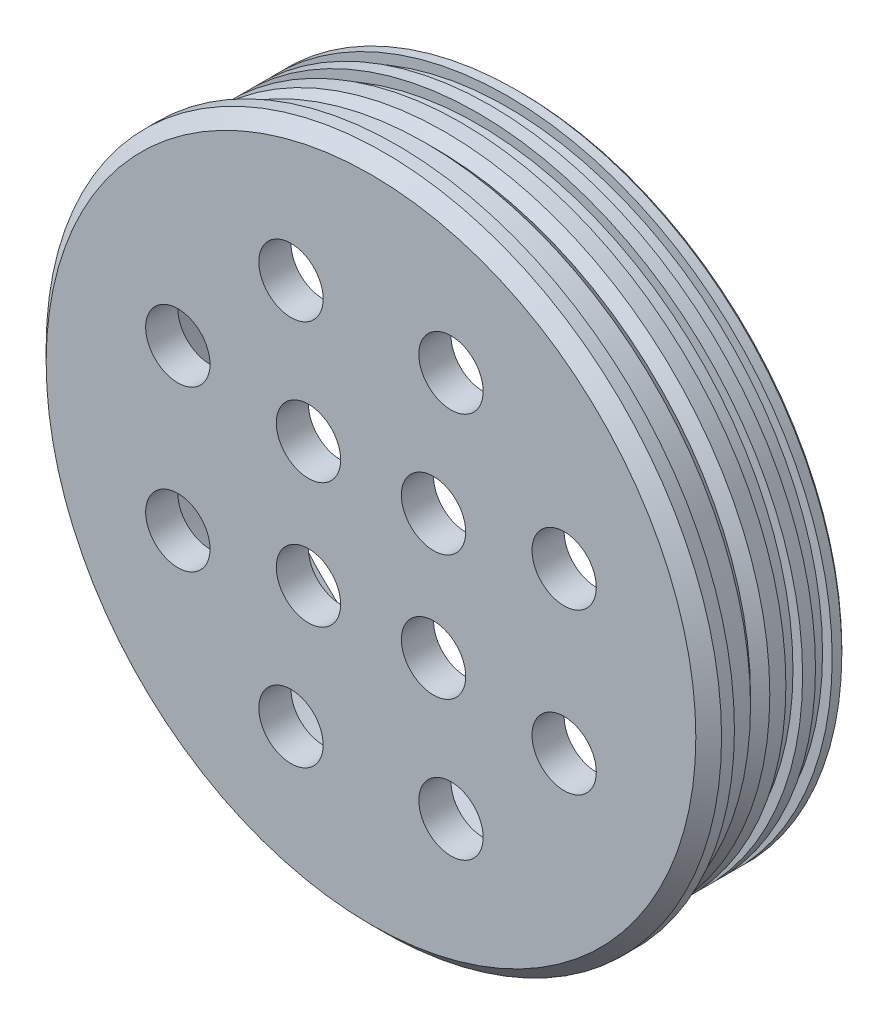
SolidWorks part; units mm, degrees
ref_plane "Спереди" through (0, 0, 0) normal (0, 0, 1) x (1, 0, 0)
ref_plane "Сверху" through (0, 0, 0) normal (0, 1, 0) x (1, 0, 0)
ref_plane "Справа" through (0, 0, 0) normal (1, 0, 0) x (0, 0, -1)
sketch "Эскиз2" plane through (0, 0, 0) normal (0, 1, 0) x (1, 0, 0)
  line L0 (0, 0) -> (0, 296960.8862) construction
  line L1 (0, 0) -> (0, 5)
  line L2 (0, 5) -> (-43.5, 5)
  line L3 (-43.5, 5) -> (-43.5, 23.2)
  line L4 (-43.5, 23.2) -> (-50, 23.2)
  line L5 (-50.5, 22.7) -> (-50.5, 21.2)
  line L6 (-50.5, 16.6) -> (-49, 16.6)
  line L7 (-49, 16.6) -> (-49, 14)
  line L8 (-49, 14) -> (-50.5, 14)
  line L9 (-50.5, 14) -> (-50.5, 11.5)
  line L10 (-18.3864, 0) -> (0, 0)
  line L11 (-50.5, 4) -> (-52.5, 4)
  line L12 (-52.5, 4) -> (-52.5, 0)
  line L13 (-52.5, 0) -> (-18.3864, 0)
  line L14 (-22, 0) -> (-2.5926, 0) construction
  line L15 (-50.5, 8.5) -> (-49, 10)
  line L16 (-49, 10) -> (-50.5, 11.5)
  line L17 (-50.5, 8.5) -> (-50.5, 4)
  line L18 (-50.5, 18.6) -> (-49, 18.6)
  line L19 (-49, 18.6) -> (-49, 21.2)
  line L20 (-49, 21.2) -> (-50.5, 21.2)
  line L21 (-50.5, 18.6) -> (-50.5, 16.6)
  line L22 (-50, 23.2) -> (-50.5, 22.7)
  line L23 (-50.5, 22.7) -> (-43.5, 22.7) construction
  line L24 (-47, 24.4497) -> (-47, 20.3957) construction
  point P8 (-50.5, 23.2)
  dimension "D2" = 5
  dimension "D3" = 105
  dimension "D4" = 1.5
  dimension "D5" = 2.6
  dimension "D6" = 1.5
  dimension "D7" = 10
  dimension "D8" = 2
  dimension "D9" = 2
  dimension "D10" = 7
  dimension "D11" = 4
  dimension "D12" = 4
  dimension "D13" = 2
  dimension "D14" = 2.6
  dimension "D15" = 1.5
  dimension "D16" = 3.5
revolve "Повернуть1" add sketch "Эскиз2" angle 360 about L0
chamfer "Фаска1" distance 2 angle 45 1 edges at (52.5, 0, 0)
sketch "Эскиз4" plane through (0, 0, 0) normal (0, 0, 1) x (1, 0, 0)
  line L0 (0, 0) -> (64.1004, 0) construction
  line L1 (30.0261, 12.4372) -> (30.0261, -12.4372) construction
  line L3 (-9.7227, -9.7227) -> (9.7227, -9.7227) construction
  line L4 (-9.7227, -9.7227) -> (-9.7227, 9.7227) construction
  line L5 (-9.7227, 9.7227) -> (9.7227, 9.7227) construction
  line L6 (9.7227, -9.7227) -> (9.7227, 9.7227) construction
  line L7 (-9.7227, -9.7227) -> (9.7227, 9.7227) construction
  line L8 (-9.7227, 9.7227) -> (9.7227, -9.7227) construction
  circle A0 centre (-12.4372, -30.0261) radius 5
  circle A1 centre (-30.0261, 12.4372) radius 5
  circle A2 centre (-12.4372, 30.0261) radius 5
  circle A3 centre (12.4372, 30.0261) radius 5
  circle A4 centre (30.0261, 12.4372) radius 5
  circle A5 centre (30.0261, -12.4372) radius 5
  circle A6 centre (12.4372, -30.0261) radius 5
  circle A7 centre (-30.0261, -12.4372) radius 5
  circle A8 centre (-9.7227, 9.7227) radius 5
  circle A9 centre (9.7227, 9.7227) radius 5
  circle A10 centre (9.7227, -9.7227) radius 5
  circle A11 centre (-9.7227, -9.7227) radius 5
  circle A12 centre (0, 0) radius 13.75 construction
  point P18 (0, 0)
  dimension "D1" = 32.5
  dimension "D2" = 10
  dimension "D3" = 10
  dimension "D5" = 27.5
  dimension "D4" = 8
extrude "Вырез-Вытянуть2" cut sketch "Эскиз4" against normal blind 10
sketch "Эскиз5" plane through (0, 0, -23.2) normal (0, 0, -1) x (-1, 0, 0)
  line L0 (0, 0) -> (0, 46.5) construction
  circle A0 centre (0, 0) radius 43.5 construction
  circle A1 centre (0, 0) radius 46.5 construction
  circle A2 centre (0, 46.5) radius 1.5
  circle A3 centre (40.2702, 23.25) radius 1.5
  circle A4 centre (40.2702, -23.25) radius 1.5
  circle A5 centre (0, -46.5) radius 1.5
  circle A6 centre (-40.2702, -23.25) radius 1.5
  circle A7 centre (-40.2702, 23.25) radius 1.5
  point P8 (42.5744, 19.9102)
  point P9 (0, 0)
  point P19 (0, 0)
  dimension "D1" = 87
  dimension "D3" = 3
  dimension "D2" = 3
  dimension "D4" = 6
extrude "Вырез-Вытянуть3" cut sketch "Эскиз5" against normal blind 10
